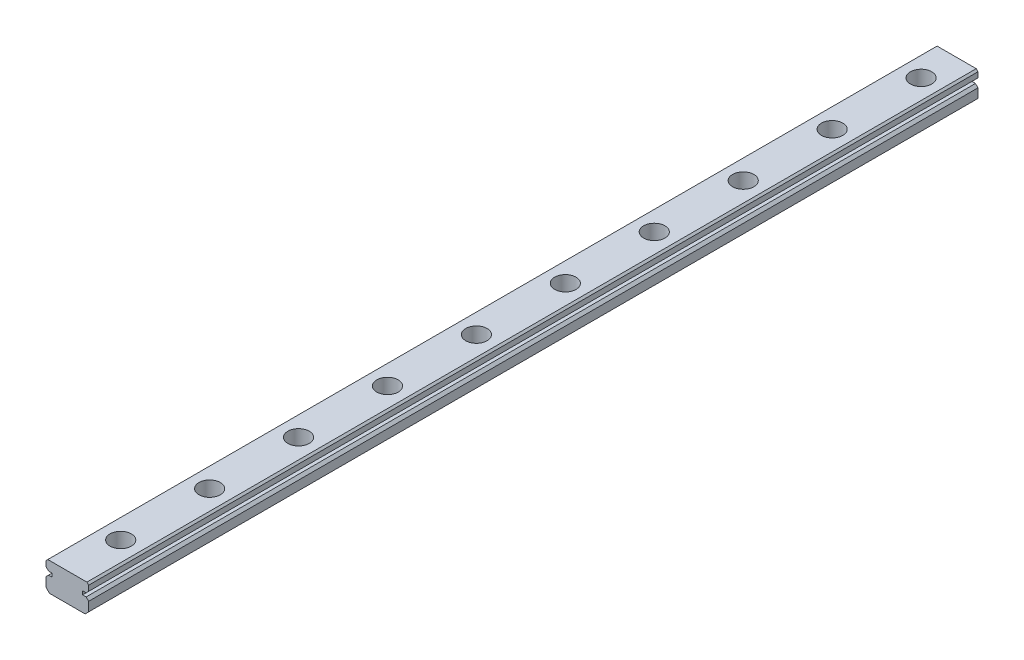
SolidWorks part; units mm, degrees
material "AISI 1020 Steel, Cold Rolled"
ref_plane "Front Plane" through (0, 0, 0) normal (0, 0, 1) x (1, 0, 0)
ref_plane "Top Plane" through (0, 0, 0) normal (0, 1, 0) x (1, 0, 0)
ref_plane "Right Plane" through (0, 0, 0) normal (1, 0, 0) x (0, 0, -1)
ref_plane "RailEndPlane" through (0, 0, 250) normal (0, 0, 1) x (1, 0, 0)
sketch "MainProfile" plane through (0, 0, 0) normal (0, 0, 1) x (1, 0, 0)
  line L0 (0, 0) -> (0, 3.5858)
  line L1 (0, 8) -> (12, 8)
  line L2 (12, 8) -> (12, 6)
  line L3 (12, 0) -> (0, 0)
  line L4 (6, 8) -> (6, -2.3077) construction
  line L5 (0, 6) -> (0.7071, 5.2929)
  line L6 (0.7071, 5.2929) -> (1.7071, 5.2929)
  line L7 (1.7071, 5.2929) -> (1.7071, 4.2929)
  line L8 (1.7071, 4.2929) -> (0.7071, 4.2929)
  line L9 (0.7071, 4.2929) -> (0, 3.5858)
  line L10 (0, 6) -> (0, 8)
  line L11 (11.2929, 4.2929) -> (12, 3.5858)
  line L12 (10.2929, 4.2929) -> (11.2929, 4.2929)
  line L13 (10.2929, 5.2929) -> (10.2929, 4.2929)
  line L14 (11.2929, 5.2929) -> (10.2929, 5.2929)
  line L15 (12, 6) -> (11.2929, 5.2929)
  line L16 (12, 3.5858) -> (12, 0)
  dimension "D1" = 8
  dimension "D2" = 12
  dimension "D3" = 270
  dimension "D4" = 1
  dimension "D5" = 2
  dimension "D6" = 2.7071
extrude "Main Extrusion" add sketch "MainProfile" along normal up to surface (250 mm away) up to plane "RailEndPlane"
sketch "First Hole Position" plane through (0, 0, 0) normal (0, 1, 0) x (1, 0, 0)
  point P0 (6, -10)
  dimension "D1" = 10
  dimension "D2" = 6
hole_wizard "Mounting Hole Master" positions "Sketch2" profile "Sketch3" legacy
sketch "Sketch2" plane through (0, 8, 0) normal (0, 1, 0) x (1, 0, 0)
  point P0 (6, -10)
sketch "Sketch3" plane through (6, 8, 10) normal (1, 0, 0) x (0, 0, 1)
  line L0 (0, 0) -> (0, 9.9216)
  line L1 (0, 9.9216) -> (1.75, 9.9216)
  line L2 (1.75, 9.9216) -> (1.75, 4.5)
  line L3 (1.75, 4.5) -> (3, 4.5)
  line L4 (3, 4.5) -> (3, 0)
  line L5 (3, 0) -> (0, 0)
  line L6 (0, 110) -> (0, -10) construction
  dimension "Diameter" = 3.5
  dimension "Depth" = 10
  dimension "C-Bore Diameter" = 6
  dimension "C-Bore Depth" = 4.5
pattern_linear "Mounting Holes Pattern" count 10 spacing 25 along (0, 0, 1) of "Mounting Hole Master"
chamfer "Rail Top Chamfer" distance 0.5 angle 45 2 edges at (0, 8, 125) (12, 8, 125)
chamfer "Rail Bottom Chamfer" distance 1 angle 45 2 edges at (0, 0, 125) (12, 0, 125)
